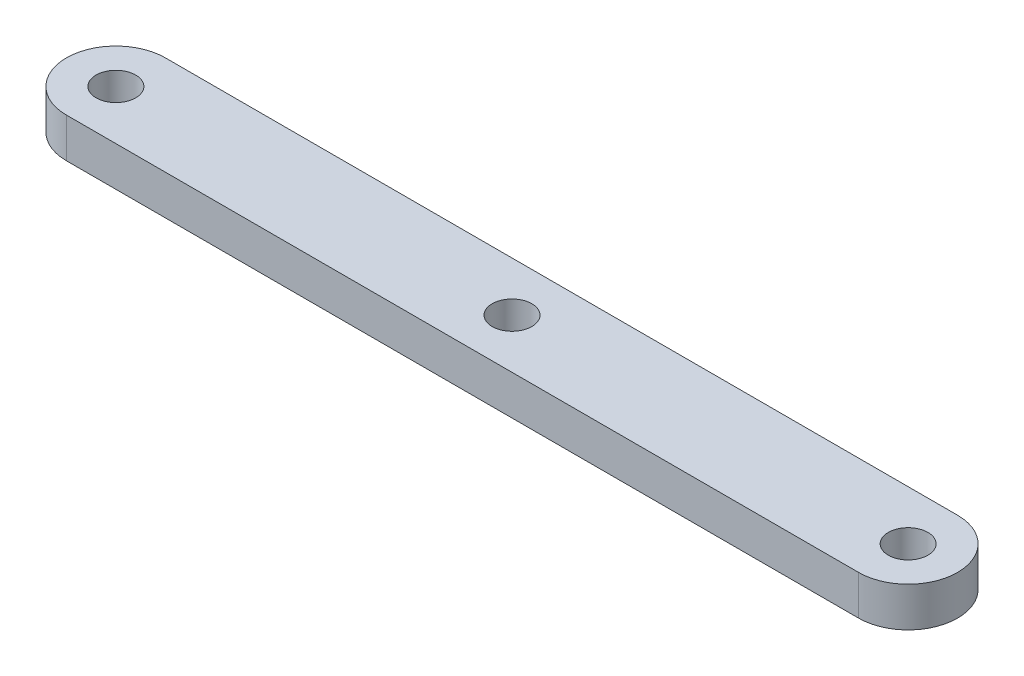
SolidWorks part; units mm, degrees
ref_plane "Front Plane" through (0, 0, 0) normal (0, 0, 1) x (1, 0, 0)
ref_plane "Top Plane" through (0, 0, 0) normal (0, 1, 0) x (1, 0, 0)
ref_plane "Right Plane" through (0, 0, 0) normal (1, 0, 0) x (0, 0, -1)
sketch "Sketch1" plane through (0, 0, 0) normal (0, 1, 0) x (1, 0, 0)
  line L0 (-20, 0) -> (20, 0) construction
  line L1 (-20, 2.5) -> (20, 2.5)
  line L2 (-20, -2.5) -> (20, -2.5)
  arc A0 (-20, 2.5) -> (-20, -2.5) centre (-20, 0) ccw
  arc A1 (20, -2.5) -> (20, 2.5) centre (20, 0) ccw
  circle A2 centre (20, 0) radius 1
  circle A3 centre (-20, 0) radius 1
  circle A4 centre (0, 0) radius 1
  point P3 (0, 0)
  dimension "D3" = 2
  dimension "D4" = 2.5
  dimension "D5" = 2
  dimension "D2" = 2
  dimension "D1" = 40
  dimension "D12" = 20
extrude "Boss-Extrude1" add sketch "Sketch1" along normal blind 2
